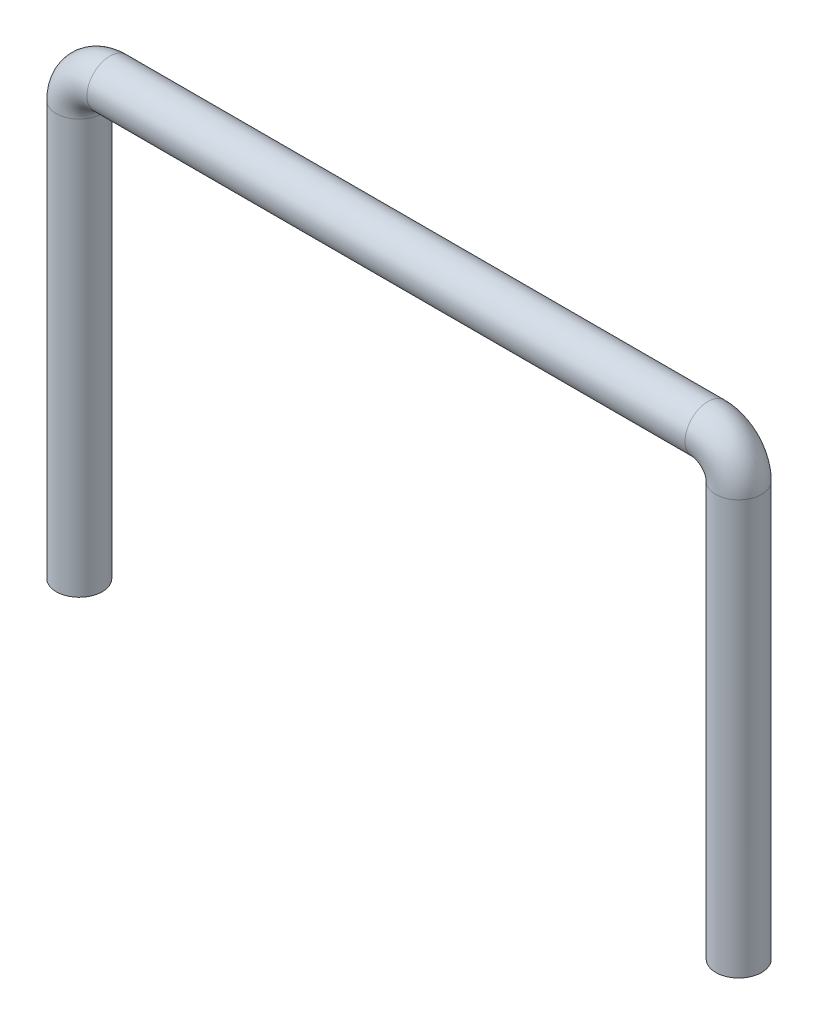
SolidWorks part; units mm, degrees
ref_plane "Front Plane" through (0, 0, 0) normal (0, 0, 1) x (1, 0, 0)
ref_plane "Top Plane" through (0, 0, 0) normal (0, 1, 0) x (1, 0, 0)
ref_plane "Right Plane" through (0, 0, 0) normal (1, 0, 0) x (0, 0, -1)
sketch "Sketch1" plane through (0, 0, 0) normal (0, 0, 1) x (1, 0, 0)
  line L0 (-130.4161, 0) -> (84.5839, 0) construction
  line L1 (-130.4161, 0) -> (-130.4161, 135)
  line L2 (-120.4161, 145) -> (74.5839, 145)
  line L3 (84.5839, 135) -> (84.5839, 0)
  arc A0 (84.5839, 135) -> (74.5839, 145) centre (74.5839, 135) ccw
  arc A1 (-130.4161, 135) -> (-120.4161, 145) centre (-120.4161, 135) cw
  point P4 (84.5839, 145)
  point P10 (-130.4161, 145)
  dimension "D3" = 10
  dimension "D1" = 145
  dimension "D2" = 145
sketch "Sketch2" plane through (0, 0, 0) normal (0, 1, 0) x (1, 0, 0)
  line L0 (-130.4161, 0) -> (84.5839, 0) construction
  circle A0 centre (-130.4161, 0) radius 7.5
  dimension "D1" = 15
sweep "Sweep1" add profiles "Sketch2" path "Sketch1"
